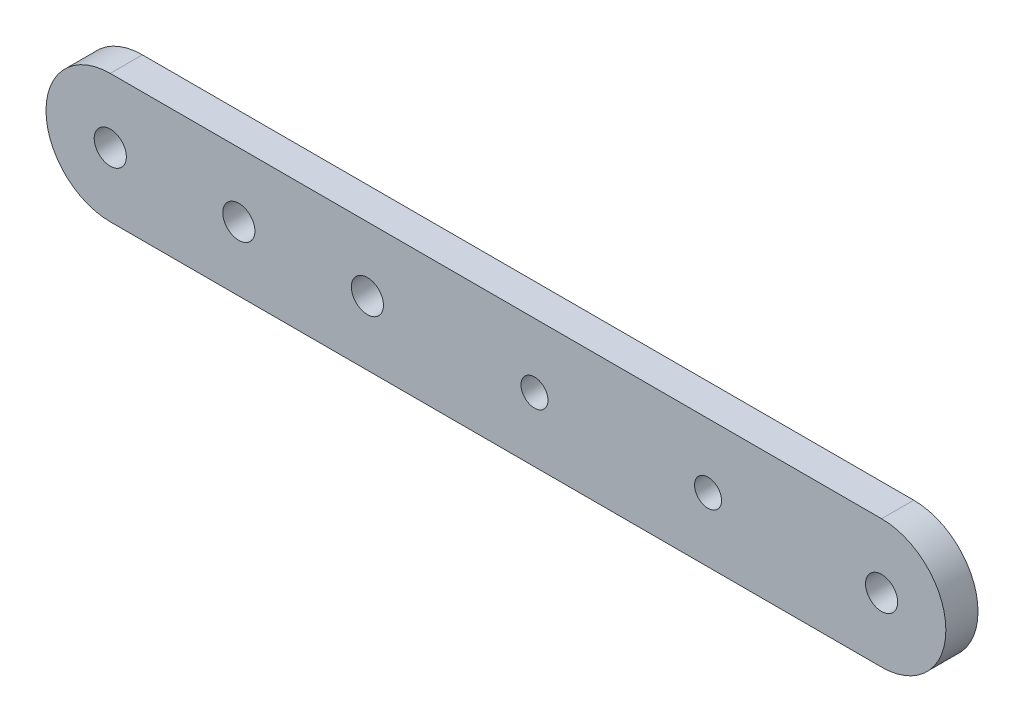
SolidWorks part; units mm, degrees
material "Alliage 1060"
ref_plane "Plan de face" through (0, 0, 0) normal (0, 0, 1) x (1, 0, 0)
ref_plane "Plan de dessus" through (0, 0, 0) normal (0, 1, 0) x (1, 0, 0)
ref_plane "Plan de droite" through (0, 0, 0) normal (1, 0, 0) x (0, 0, -1)
sketch "Esquisse1" plane through (0, 0, 0) normal (0, 0, 1) x (1, 0, 0)
  line L4 (60, 10) -> (-60, 10)
  line L5 (-60, -10) -> (60, -10)
  line L6 (60, 10) -> (-60, 10)
  line L7 (-60, -10) -> (60, -10)
  circle A6 centre (33, 0) radius 2.1 construction
  circle A7 centre (6, 0) radius 2.1 construction
  arc A8 (-60, 10) -> (-60, -10) centre (-60, 0) ccw
  arc A9 (60, -10) -> (60, 10) centre (60, 0) ccw
  arc A10 (-60, 10) -> (-60, -10) centre (-60, 0) ccw
  arc A11 (60, -10) -> (60, 10) centre (60, 0) ccw
  circle A12 centre (60, 0) radius 2.5
  circle A13 centre (-60, 0) radius 2.5
  circle A14 centre (-60, 0) radius 1.5 construction
  circle A15 centre (60, 0) radius 1.5 construction
  circle A16 centre (33, 0) radius 2.1
  circle A17 centre (6, 0) radius 2.1
  circle A28 centre (-40, 0) radius 2.5
  circle A29 centre (-20, 0) radius 2.5
  circle A30 centre (-40, 0) radius 2.9 construction
  circle A31 centre (-20, 0) radius 2.9 construction
  dimension "D1" = 0
  dimension "D2" = 5
extrude "Extrusion1" add sketch "Esquisse1" along normal blind 5
